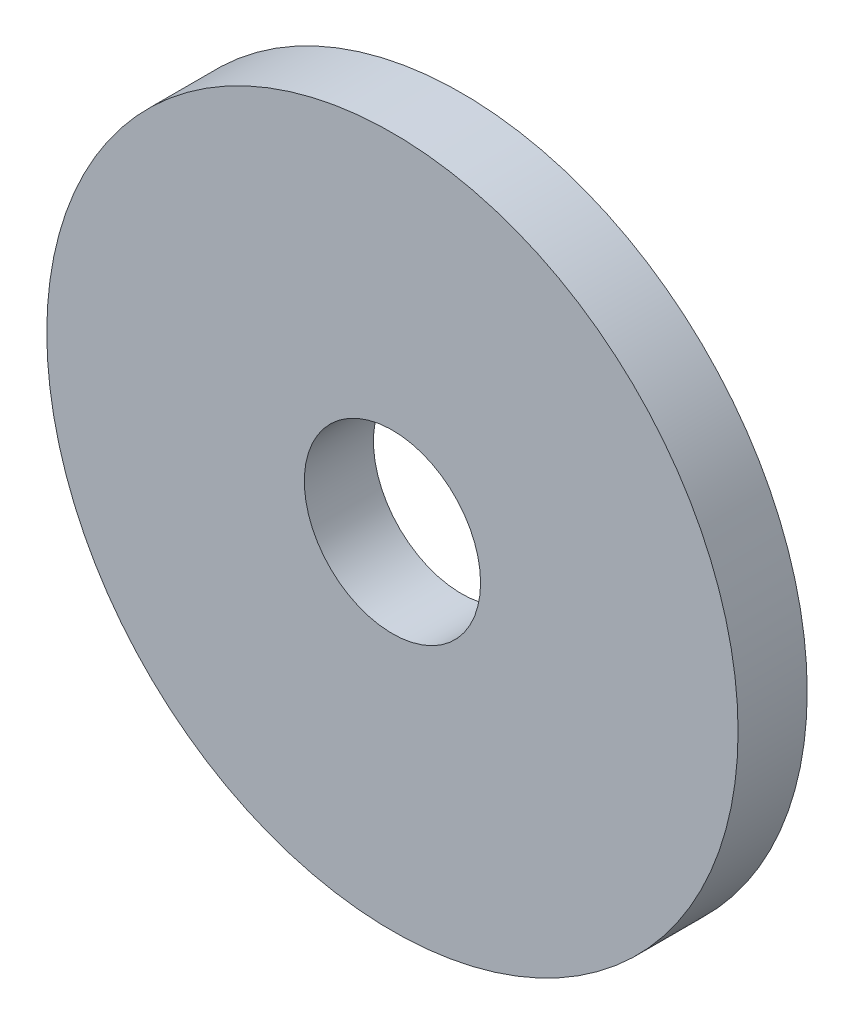
SolidWorks part; units mm, degrees
ref_plane "Front Plane" through (0, 0, 0) normal (0, 0, 1) x (1, 0, 0)
ref_plane "Top Plane" through (0, 0, 0) normal (0, 1, 0) x (1, 0, 0)
ref_plane "Right Plane" through (0, 0, 0) normal (1, 0, 0) x (0, 0, -1)
sketch "Sketch1" plane through (0, 0, 0) normal (0, 0, 1) x (1, 0, 0)
  circle A0 centre (0, 0) radius 10
  circle A1 centre (0, 0) radius 2.55
  dimension "D1" = 20
  dimension "D2" = 5.1
extrude "Boss-Extrude1" add sketch "Sketch1" along normal blind 2
